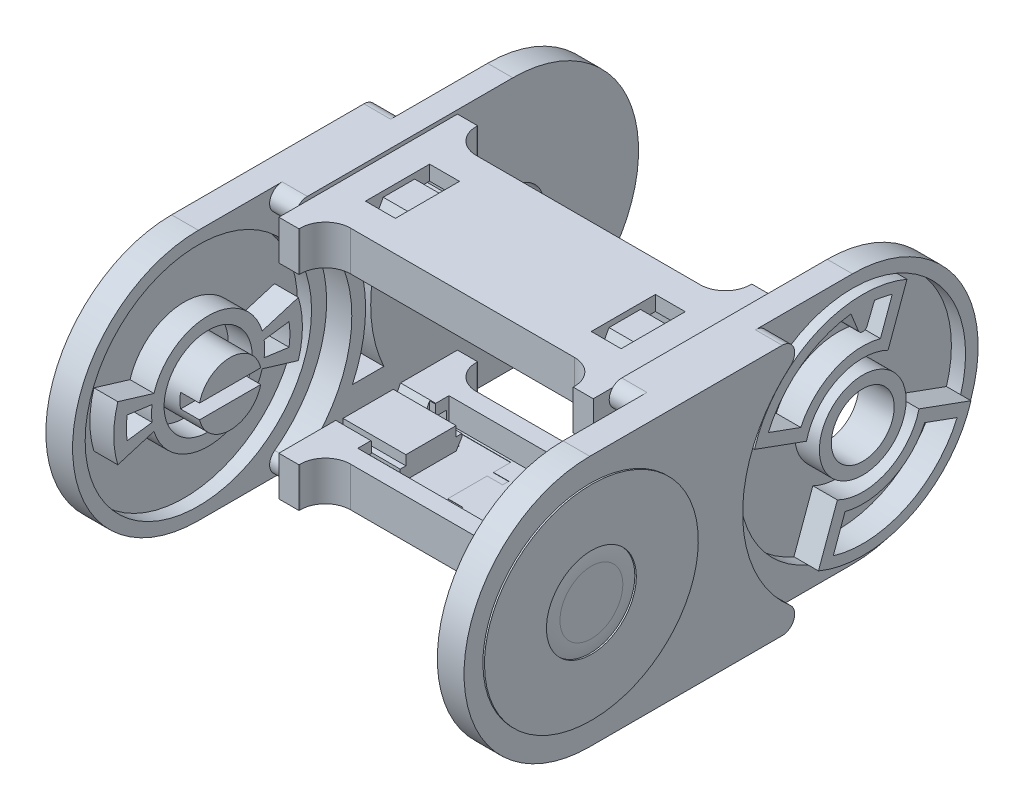
SolidWorks part; units mm, degrees
material "ABS"
ref_plane "Front Plane" through (0, 0, 0) normal (0, 0, 1) x (1, 0, 0)
ref_plane "Top Plane" through (0, 0, 0) normal (0, 1, 0) x (1, 0, 0)
ref_plane "Right Plane" through (0, 0, 0) normal (1, 0, 0) x (0, 0, -1)
other "Configuration Table"
ref_plane "Plane1" through (31.25, 0, 0) normal (1, 0, 0) x (0, 0, -1)
sketch "Sketch1" plane through (31.25, 0, 0) normal (1, 0, 0) x (0, 0, -1)
  line L0 (0, 0) -> (46, 0) construction
  line L1 (0, 20) -> (30.5828, 20)
  line L2 (0, -20) -> (30.5828, -20)
  line L3 (46, 20) -> (46, -20) construction
  arc A0 (0, 20) -> (0, -20) centre (0, 0) ccw
  circle A2 centre (0, 0) radius 5
  arc A7 (31.8838, 16.481) -> (31.8838, -16.481) centre (46, 0) ccw
  arc A8 (30.5828, -20) -> (31.8838, -16.481) centre (30.5828, -18) ccw
  arc A9 (31.8838, 16.481) -> (30.5828, 20) centre (30.5828, 18) ccw
  point P6 (0, 0)
  point P8 (0, 0)
  dimension "D2" = 40
  dimension "D3" = 10
  dimension "D4" = 21.7
  dimension "D5" = 2
  dimension "D1" = 46
extrude "Boss-Extrude1" add sketch "Sketch1" along normal blind 2
sketch "Sketch2" plane through (33.25, 0, 0) normal (1, 0, 0) x (0, 0, -1)
  circle A0 centre (0, 0) radius 7.15
  ellipse E0 centre (0, 0) end of major axis (-17, 0) minor radius 16.25
  dimension "D3" = 14.3
  dimension "D1" = 34
  dimension "D2" = 32.5
extrude "Boss-Extrude2" add sketch "Sketch2" along normal blind 0.25
sketch "Sketch3" plane through (31.25, 0, 0) normal (-1, 0, 0) x (0, 0, 1)
  line L4 (-30.5828, -20) -> (0, -20)
  line L5 (0, 20) -> (-30.5828, 20)
  line L6 (-30.5828, -20) -> (0, -20)
  line L7 (0, 20) -> (-30.5828, 20)
  circle A4 centre (0, 0) radius 18
  arc A8 (-30.5828, 20) -> (-31.8838, 16.481) centre (-30.5828, 18) ccw
  arc A9 (0, -20) -> (0, 20) centre (0, 0) ccw
  arc A10 (-30.5828, 20) -> (-31.8838, 16.481) centre (-30.5828, 18) ccw
  arc A11 (-31.8838, -16.481) -> (-31.8838, 16.481) centre (-46, 0) ccw
  arc A13 (0, -20) -> (0, 20) centre (0, 0) ccw
  arc A17 (-31.8838, -16.481) -> (-31.8838, 16.481) centre (-46, 0) ccw
  arc A18 (-31.8838, -16.481) -> (-30.5828, -20) centre (-30.5828, -18) ccw
  arc A19 (-31.8838, -16.481) -> (-30.5828, -20) centre (-30.5828, -18) ccw
  dimension "D2" = 2
  dimension "D1" = 0
extrude "Boss-Extrude3" add sketch "Sketch3" along normal blind 2.25
sketch "Sketch5" plane through (31.25, 0, 0) normal (-1, 0, 0) x (0, 0, 1)
  line L0 (-20.8019, 0) -> (21.6225, 0) construction
  line L1 (-12.8779, 1.7773) -> (-8.9155, 1.2305)
  line L2 (-8.6132, 2.61) -> (-14.3554, 4.35)
  line L3 (-8.9155, 1.2305) -> (0, 0) construction
  line L4 (-8.6132, 2.61) -> (0, 0) construction
  line L5 (-8.6132, -2.61) -> (-14.3554, -4.35)
  line L6 (-12.8779, -1.7773) -> (-8.9155, -1.2305)
  line L7 (0, -21.0754) -> (0, 22.5568) construction
  line L8 (12.8779, -1.7773) -> (8.9155, -1.2305)
  line L9 (8.6132, -2.61) -> (14.3554, -4.35)
  line L10 (8.6132, 2.61) -> (14.3554, 4.35)
  line L11 (12.8779, 1.7773) -> (8.9155, 1.2305)
  arc A0 (-8.9155, 1.2305) -> (-8.9155, -1.2305) centre (0, 0) ccw
  circle A1 centre (0, 0) radius 7
  arc A2 (-14.3554, 4.35) -> (-14.3554, -4.35) centre (0, 0) ccw
  arc A3 (-12.8779, 1.7773) -> (-12.8779, -1.7773) centre (0, 0) ccw
  arc A4 (-8.6132, -2.61) -> (8.6132, -2.61) centre (0, 0) ccw
  arc A5 (12.8779, 1.7773) -> (12.8779, -1.7773) centre (0, 0) cw
  arc A6 (14.3554, 4.35) -> (14.3554, -4.35) centre (0, 0) cw
  arc A7 (8.6132, 2.61) -> (-8.6132, 2.61) centre (0, 0) ccw
  arc A8 (8.9155, -1.2305) -> (8.9155, 1.2305) centre (0, 0) ccw
  dimension "D1" = 14
  dimension "D2" = 18
  dimension "D3" = 26
  dimension "D4" = 30
  dimension "D5" = 9
  dimension "D6" = 8.7
extrude "Boss-Extrude4" add sketch "Sketch5" along normal blind 3.8
sketch "Sketch6" plane through (29, 0, 0) normal (1, 0, 0) x (0, 0, -1)
  line L0 (13.3327, 20) -> (46, 20)
  line L1 (13.3327, -20) -> (46, -20)
  line L2 (46, 0) -> (0, 0) construction
  line L3 (30.5828, 20) -> (0, 20) construction
  line L4 (0, -20) -> (30.5828, -20) construction
  line L5 (-20, 0) -> (0, 0) construction
  arc A1 (46, -20) -> (46, 20) centre (46, 0) ccw
  arc A2 (12.1422, -16.3929) -> (12.1422, 16.3929) centre (0, 0) ccw
  arc A3 (13.3327, -20) -> (12.1422, -16.3929) centre (13.3327, -18) cw
  arc A4 (13.3327, 20) -> (12.1422, 16.3929) centre (13.3327, 18) ccw
  circle A5 centre (46, 0) radius 5
  circle A6 centre (0, 0) radius 5 construction
  arc A11 (0, 20) -> (0, -20) centre (0, 0) ccw construction
  point P19 (4.02, -20)
  point P22 (4.02, 20)
  dimension "D2" = 40.4
  dimension "D3" = 2
  dimension "D1" = 46
extrude "Boss-Extrude5" add sketch "Sketch6" against normal blind 4
sketch "Sketch7" plane through (29, 0, 0) normal (1, 0, 0) x (0, 0, -1)
  circle A0 centre (46, 0) radius 18
  arc A2 (46, -20) -> (46, 20) centre (46, 0) ccw construction
  dimension "D1" = 2
extrude "Cut-Extrude1" cut sketch "Sketch7" against normal blind 2.25
sketch "Sketch8" plane through (26.75, 0, 0) normal (1, 0, 0) x (0, 0, -1)
  line L0 (50.6899, 15.6629) -> (48.8125, 10.505)
  line L1 (53.0405, 16.566) -> (50.0311, 8.2977)
  line L2 (44.2899, -4.6985) -> (47.7101, 4.6985) construction
  line L3 (46, 0) -> (73.2087, 0) construction
  line L4 (46, 0) -> (41.3015, 1.7101) construction
  line L5 (37.0525, 2.2457) -> (28.7842, 5.2551)
  line L6 (30.9869, 6.4753) -> (36.1448, 4.598)
  line L7 (46, 0) -> (41.4685, -2.1131) construction
  line L8 (41.3101, -15.6629) -> (43.1875, -10.505)
  line L9 (41.9689, -8.2977) -> (38.9595, -16.566)
  line L10 (63.2158, -5.2551) -> (54.9475, -2.2457)
  line L11 (61.0131, -6.4753) -> (55.8552, -4.598)
  circle A0 centre (46, 0) radius 5
  circle A1 centre (46, 0) radius 6.9
  circle A2 centre (46, 0) radius 5 construction
  arc A3 (50.0311, 8.2977) -> (37.0525, 2.2457) centre (46, 0) ccw
  arc A6 (53.0405, 16.566) -> (28.7842, 5.2551) centre (46, 0) ccw
  circle A8 centre (46, 0) radius 18 construction
  arc A9 (48.8125, 10.505) -> (36.1448, 4.598) centre (46, 0) ccw
  arc A10 (50.6899, 15.6629) -> (30.9869, 6.4753) centre (46, 0) ccw
  arc A11 (61.0131, -6.4753) -> (41.3101, -15.6629) centre (46, 0) cw
  arc A12 (55.8552, -4.598) -> (43.1875, -10.505) centre (46, 0) cw
  arc A13 (63.2158, -5.2551) -> (38.9595, -16.566) centre (46, 0) cw
  arc A14 (54.9475, -2.2457) -> (41.9689, -8.2977) centre (46, 0) cw
  dimension "D1" = 13.8
  dimension "D2" = 18.45
  dimension "D5" = 70
  dimension "D6" = 1.9
  dimension "D7" = 90
  dimension "D8" = 1.9
  dimension "D4" = 1.65
  dimension "D3" = 1.65
  dimension "D9" = 45
extrude "Boss-Extrude6" add sketch "Sketch8" along normal blind 3.9
sketch "Sketch9" plane through (30.65, 0, 0) normal (1, 0, 0) x (0, 0, -1)
  line L0 (46, 0) -> (46, 18) construction
  line L1 (44.125, 16.2421) -> (45.3045, 13.3193)
  line L2 (47.875, 16.2421) -> (46.6955, 13.3193)
  arc A0 (53.0405, 16.566) -> (28.7842, 5.2551) centre (46, 0) ccw construction
  arc A1 (50.6899, 15.6629) -> (30.9869, 6.4753) centre (46, 0) ccw construction
  arc A2 (45.3045, 13.3193) -> (46.6955, 13.3193) centre (46, 13.6) ccw
  arc A3 (44.125, 16.2421) -> (47.875, 16.2421) centre (46, 0) cw
  dimension "D1" = 0.75
  dimension "D2" = 3.5
  dimension "D3" = 3.75
extrude "Boss-Extrude7" add sketch "Sketch9" against normal up to next
sketch "Sketch10" plane through (25, 0, 0) normal (-1, 0, 0) x (0, 0, 1)
  line L0 (-46, 0) -> (0, 0) construction
  line L1 (-23, 0) -> (-23, 29.3467) construction
  line L2 (-25.5, 9.5) -> (-20.5, 9.5)
  line L3 (-25.5, -9.5) -> (-20.5, -9.5)
  arc A0 (-25.5, 9.5) -> (-25.5, -9.5) centre (-46, 0) cw
  arc A1 (-20.5, 9.5) -> (-20.5, -9.5) centre (0, 0) ccw
  point P12 (-25.5, 9.5)
  point P13 (-25.5, -9.5)
  point P19 (-23, 9.5)
  point P22 (-20.5, -9.5)
  point P23 (-20.5, 9.5)
  point P24 (-23, -9.5)
  dimension "D1" = 19
  dimension "D2" = 5
extrude "Cut-Extrude2" cut sketch "Sketch10" against normal blind 6.3
sketch "Sketch11" plane through (25, 0, 0) normal (-1, 0, 0) x (0, 0, 1)
  line L0 (-23, 0) -> (-23, 21.8907) construction
  line L3 (-46, 0) -> (0, 0) construction
  line L4 (-27, 13.4) -> (-27, 14.94)
  line L5 (-27, 13.4) -> (-19, 13.4)
  line L6 (-27, 14.94) -> (-27.9, 14.94)
  line L7 (-27.9, 14.94) -> (-27.9, 15.44)
  line L8 (-27.9, 15.44) -> (-27, 16.9)
  line L9 (-27, 16.9) -> (-19, 16.9)
  line L10 (-18.1, 15.44) -> (-19, 16.9)
  line L11 (-18.1, 14.94) -> (-18.1, 15.44)
  line L12 (-19, 14.94) -> (-18.1, 14.94)
  line L13 (-19, 13.4) -> (-19, 14.94)
  line L14 (-19, -13.4) -> (-19, -14.94)
  line L15 (-19, -14.94) -> (-18.1, -14.94)
  line L16 (-18.1, -14.94) -> (-18.1, -15.44)
  line L17 (-18.1, -15.44) -> (-19, -16.9)
  line L18 (-27, -16.9) -> (-19, -16.9)
  line L19 (-27.9, -15.44) -> (-27, -16.9)
  line L20 (-27.9, -14.94) -> (-27.9, -15.44)
  line L21 (-27, -14.94) -> (-27.9, -14.94)
  line L22 (-27, -13.4) -> (-19, -13.4)
  line L23 (-27, -13.4) -> (-27, -14.94)
  dimension "D1" = 1.54
  dimension "D2" = 26.8
  dimension "D3" = 33.8
  dimension "D4" = 8
  dimension "D5" = 9.8
  dimension "D6" = 0.5
extrude "Boss-Extrude8" add sketch "Sketch11" along normal blind 10
sketch "Sketch13" plane through (0, 16.9, 0) normal (0, 1, 0) x (1, 0, 0)
  line L0 (15.8, 30.3851) -> (15.8, 15.9317) construction
  line L1 (15, 19) -> (15, 27) construction
  dimension "D1" = 0.8
ref_plane "Plane2" through (15.8, 0, 0) normal (-1, 0, 0) x (0, 0, 1)
sketch "Sketch15" plane through (15.8, 0, 0) normal (-1, 0, 0) x (0, 0, 1)
  line L0 (-23, 13.4) -> (-23, 20.5432) construction
  line L1 (-27, 13.4) -> (-19, 13.4) construction
  line L2 (-25.5, 18.75) -> (-20.5, 18.75)
  line L3 (-20.5, 18.75) -> (-19.5, 16.9)
  line L4 (-30.3851, 16.9) -> (-15.9317, 16.9) construction
  line L5 (-19.5, 16.9) -> (-26.5, 16.9)
  line L6 (-25.5, 18.75) -> (-26.5, 16.9)
  line L7 (-46, 20) -> (-13.3327, 20) construction
  dimension "D1" = 7
  dimension "D2" = 5
  dimension "D3" = 1.85
  dimension "D4" = 1.25
extrude "Boss-Extrude9" add sketch "Sketch15" against normal blind 4.3
mirror "Mirror1" about plane through (0, 0, 0) normal (0, 1, 0) of "Boss-Extrude9"
mirror "Mirror2" about plane through (0, 0, 0) normal (1, 0, 0) of bodies 114
ref_plane "Plane3" through (0, 19.4, 0) normal (0, 1, 0) x (1, 0, 0)
sketch "Sketch17" plane through (0, 19.4, 0) normal (0, 1, 0) x (1, 0, 0)
  line L0 (0, 0) -> (0, 46) construction
  line L1 (-25, 23) -> (25, 23) construction
  line L2 (-25, 19) -> (-25, 27) construction
  line L3 (25, 19) -> (25, 27) construction
  line L4 (21.8, 9) -> (21.8, 8.8)
  line L5 (17.8, 13) -> (-17.8, 13)
  line L7 (17.8, 33) -> (-17.8, 33)
  line L9 (21.8, 13) -> (-21.8, 33) construction
  line L10 (21.8, 33) -> (-21.8, 13) construction
  line L11 (21.8, 37.2) -> (25, 37.2)
  line L12 (21.8, 37.2) -> (21.8, 37)
  line L13 (21.8, 8.8) -> (25, 8.8)
  line L14 (25, 37.2) -> (25, 8.8)
  line L15 (-25, 37.2) -> (-25, 8.8)
  line L16 (-21.8, 8.8) -> (-25, 8.8)
  line L17 (-21.8, 37.2) -> (-21.8, 37)
  line L18 (-21.8, 37.2) -> (-25, 37.2)
  line L19 (-21.8, 9) -> (-21.8, 8.8)
  line L20 (-15.8, 25.5) -> (-20.1, 20.5) construction
  line L21 (20.325, 17.9) -> (15.575, 17.9)
  line L22 (-20.325, 17.9) -> (-15.575, 17.9)
  line L23 (-20.325, 17.9) -> (-20.325, 28.1)
  line L24 (-20.325, 28.1) -> (-15.575, 28.1)
  line L25 (-15.575, 17.9) -> (-15.575, 28.1)
  line L26 (-20.325, 17.9) -> (-15.575, 28.1) construction
  line L27 (-20.325, 28.1) -> (-15.575, 17.9) construction
  line L28 (15.575, 17.9) -> (15.575, 28.1)
  line L29 (20.325, 17.9) -> (20.325, 28.1)
  line L30 (20.325, 28.1) -> (15.575, 28.1)
  arc A0 (21.8, 37) -> (17.8, 33) centre (17.8, 37) cw
  arc A1 (17.8, 13) -> (21.8, 9) centre (17.8, 9) cw
  arc A2 (-17.8, 13) -> (-21.8, 9) centre (-17.8, 9) ccw
  arc A3 (-17.8, 33) -> (-21.8, 37) centre (-17.8, 37) cw
  point P4 (0, 23)
  point P10 (0, 23)
  point P39 (-17.95, 23)
  point P40 (-17.95, 23)
  dimension "D5" = 4
  dimension "D1" = 28.4
  dimension "D2" = 3.2
  dimension "D3" = 20
  dimension "D4" = 50
  dimension "D6" = 10.2
  dimension "D7" = 4.75
extrude "Boss-Extrude10" add sketch "Sketch17" against normal blind 6.3 separate body
sketch "Sketch18" plane through (25, 0, 0) normal (1, 0, 0) x (0, 0, -1)
  line L0 (23, 13.1) -> (23, 19.4) construction
  line L1 (8.8, 13.1) -> (37.2, 13.1) construction
  line L2 (4.5375, 19.4) -> (-4.5375, 19.4) construction
  line L4 (29.89, 14.9) -> (16.11, 14.9)
  line L5 (29.89, 14.9) -> (29.89, 17.05)
  line L6 (29.89, 17.05) -> (16.11, 17.05)
  line L7 (16.11, 14.9) -> (16.11, 17.05)
  line L8 (29.89, 14.9) -> (16.11, 17.05) construction
  line L9 (29.89, 17.05) -> (16.11, 14.9) construction
  point P6 (23, 15.975)
  dimension "D1" = 13.78
  dimension "D2" = 2.15
  dimension "D3" = 2.35
extrude "Cut-Extrude3" cut sketch "Sketch18" against normal blind 15.8
sketch "Sketch19" plane through (25, 0, 0) normal (1, 0, 0) x (0, 0, -1)
  line L0 (23, 14.9) -> (23, 13.1) construction
  line L1 (16.11, 14.9) -> (29.89, 14.9) construction
  line L2 (8.8, 13.1) -> (37.2, 13.1) construction
  line L3 (18.8, 14.9) -> (17.85, 13.1)
  line L4 (17.85, 13.1) -> (28.15, 13.1)
  line L5 (28.15, 13.1) -> (27.2, 14.9)
  line L6 (27.2, 14.9) -> (18.8, 14.9)
  dimension "D1" = 10.3
  dimension "D2" = 8.4
extrude "Cut-Extrude4" cut sketch "Sketch19" against normal blind 11.25
sketch "Sketch20" plane through (0, 13.1, 0) normal (0, -1, 0) x (1, 0, 0)
  line L0 (13.75, -23) -> (13.5581, -23) construction
  line L1 (13.75, -17.85) -> (13.75, -28.15) construction
  line L2 (6.75, -27.125) -> (6.75, -26.125)
  line L3 (13.75, -18.875) -> (6.75, -18.875)
  line L4 (13.75, -18.875) -> (13.75, -19.875)
  line L5 (13.75, -19.875) -> (6.75, -19.875)
  line L6 (6.75, -18.875) -> (6.75, -19.875)
  line L7 (13.75, -26.125) -> (6.75, -26.125)
  line L8 (13.75, -27.125) -> (13.75, -26.125)
  line L9 (13.75, -27.125) -> (6.75, -27.125)
  dimension "D1" = 6.25
  dimension "D2" = 8.25
  dimension "D3" = 7
extrude "Cut-Extrude5" cut sketch "Sketch20" against normal up to surface (3.95 mm away)
mirror "Mirror5" about plane through (0, 0, 0) normal (1, 0, 0) of "Cut-Extrude5", "Cut-Extrude4", "Cut-Extrude3"
sketch "Sketch21" plane through (0, 13.1, 0) normal (0, -1, 0) x (1, 0, 0)
  line L0 (0, -13) -> (0, -33) construction
  line L1 (-17.8, -13) -> (17.8, -13) construction
  line L2 (17.8, -33) -> (-17.8, -33) construction
  line L4 (19.4, -30.25) -> (-19.4, -30.25)
  line L5 (19.4, -30.25) -> (19.4, -15.75)
  line L6 (19.4, -15.75) -> (-19.4, -15.75)
  line L7 (-19.4, -30.25) -> (-19.4, -15.75)
  line L8 (19.4, -30.25) -> (-19.4, -15.75) construction
  line L9 (19.4, -15.75) -> (-19.4, -30.25) construction
  point P6 (0, -23)
  dimension "D1" = 38.8
  dimension "D2" = 14.5
extrude "Cut-Extrude6" cut sketch "Sketch21" against normal blind 3.9
mirror "Mirror4" about plane through (0, 0, 0) normal (0, 1, 0) of bodies 122 116
sketch "Sketch23" plane through (0, 0, 0) normal (0, 1, 0) x (1, 0, 0)
  line L0 (-23.95, 0) -> (-33.5, 0)
  line L2 (-33.5, 17) -> (-33.5, -17) construction
  line L3 (-33.5, 0) -> (-33.5, 5)
  line L4 (-33.25, 30.5828) -> (-33.25, 0) construction
  line L5 (-33.25, 5) -> (-23.95, 5)
  line L6 (-23.95, 5) -> (-23.95, 0)
  line L7 (-33.25, 7.2) -> (-33.25, 5)
  arc A0 (-33.5, 5) -> (-33.25, 7.2) centre (-23.695, 5) cw
  dimension "D1" = 7.2
  dimension "D2" = 9.55
  dimension "D3" = 5
revolve "Revolve1" add sketch "Sketch23" angle 360 about L0
sketch "Sketch24" plane through (-23.95, 0, 0) normal (1, 0, 0) x (0, 0, -1)
  line L1 (5, -1.15) -> (-5, -1.15)
  line L2 (5, -1.15) -> (5, 1.15)
  line L3 (5, 1.15) -> (-5, 1.15)
  line L4 (-5, -1.15) -> (-5, 1.15)
  line L5 (5, -1.15) -> (-5, 1.15) construction
  line L6 (5, 1.15) -> (-5, -1.15) construction
  circle A0 centre (0, 0) radius 5 construction
  point P0 (0, 0)
  dimension "D1" = 2.3
extrude "Cut-Extrude7" cut sketch "Sketch24" against normal blind 3
mirror "Mirror6" about plane through (0, 0, 0) normal (1, 0, 0) of bodies 125 123
equation "\"D8@Sketch8\"=\"D6@Sketch8\""
equation "\"D3@Sketch8\"=\"D4@Sketch8\""
